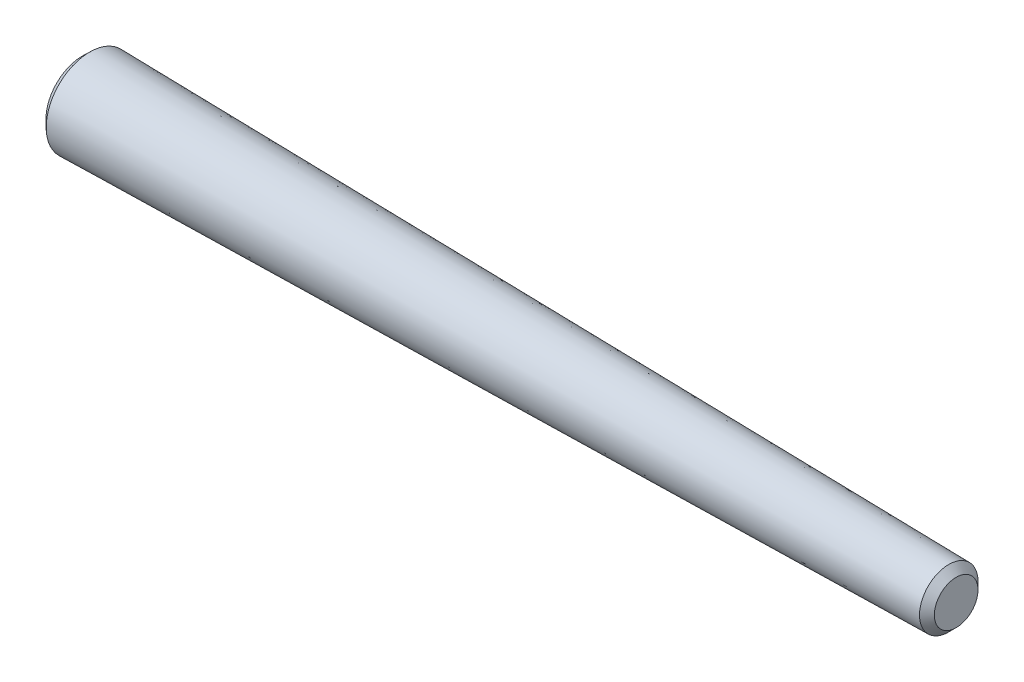
SolidWorks part; units mm, degrees
ref_plane "Front Plane" through (0, 0, 0) normal (0, 0, 1) x (1, 0, 0)
ref_plane "Top Plane" through (0, 0, 0) normal (0, 1, 0) x (1, 0, 0)
ref_plane "Right Plane" through (0, 0, 0) normal (1, 0, 0) x (0, 0, -1)
sketch "Sketch1" plane through (0, 0, 0) normal (0, 0, 1) x (1, 0, 0)
  line L0 (0, 0) -> (60, 0) construction
  line L1 (0, 0) -> (0, 3)
  line L2 (0, 3) -> (60, 2)
  line L3 (60, 2) -> (60, 0)
  line L4 (0, 0) -> (60, 0)
  dimension "D1" = 60
  dimension "D2" = 6
  dimension "D3" = 4
revolve "Revolve1" add sketch "Sketch1" angle 360 about L0
chamfer "Chamfer1" distance 0.5 angle 45 2 edges at (60, 0, 2) (0, 0, 3)
